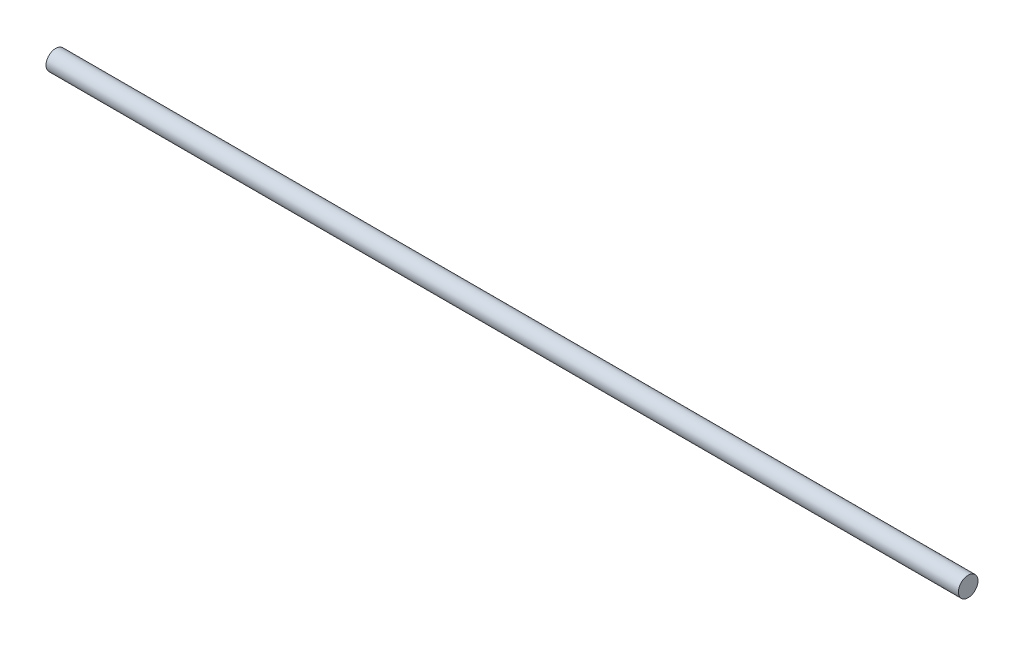
SolidWorks part; units mm, degrees
ref_plane "Front Plane" through (0, 0, 0) normal (0, 0, 1) x (1, 0, 0)
ref_plane "Top Plane" through (0, 0, 0) normal (0, 1, 0) x (1, 0, 0)
ref_plane "Right Plane" through (0, 0, 0) normal (1, 0, 0) x (0, 0, -1)
sketch "Sketch1" plane through (0, 0, 0) normal (1, 0, 0) x (0, 0, -1)
  circle A0 centre (0, 0) radius 1.5
  dimension "D1" = 3
extrude "Boss-Extrude1" add sketch "Sketch1" along normal mid plane 140
